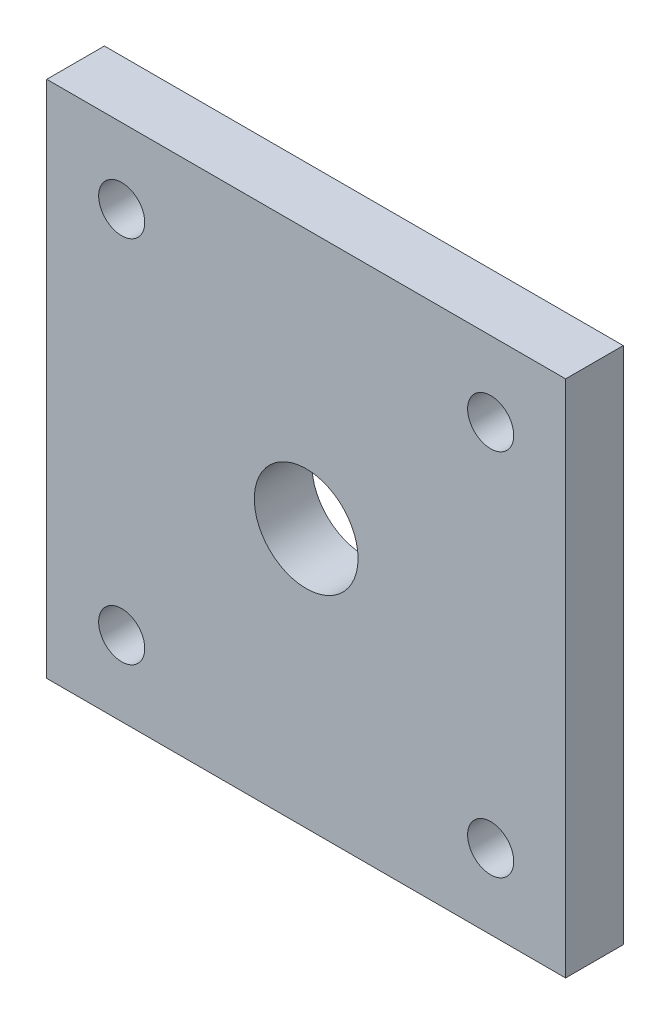
SolidWorks part; units mm, degrees
ref_plane "Front Plane" through (0, 0, 0) normal (0, 0, 1) x (1, 0, 0)
ref_plane "Top Plane" through (0, 0, 0) normal (0, 1, 0) x (1, 0, 0)
ref_plane "Right Plane" through (0, 0, 0) normal (1, 0, 0) x (0, 0, -1)
sketch "Sketch1" plane through (0, 0, 0) normal (0, 0, 1) x (1, 0, 0)
  line L1 (-22.5, -22.5) -> (22.5, -22.5)
  line L2 (-22.5, -22.5) -> (-22.5, 22.5)
  line L3 (-22.5, 22.5) -> (22.5, 22.5)
  line L4 (22.5, -22.5) -> (22.5, 22.5)
  line L5 (-22.5, -22.5) -> (22.5, 22.5) construction
  line L6 (-22.5, 22.5) -> (22.5, -22.5) construction
  circle A0 centre (0, 0) radius 4.5
  point P0 (0, 0)
  dimension "D3" = 9
  dimension "D1" = 45
  dimension "D2" = 45
extrude "Boss-Extrude1" add sketch "Sketch1" along normal blind 5
extrude "Cut-Extrude1" cut sketch "Sketch2" against normal through all
sketch "Sketch2" plane through (-496.0375, -95.1348, 0) normal (0, 0, -1) x (-1, 0, 0)
  arc A8 (-510.0375, 79.1348) -> (-514.0375, 79.1348) centre (-512.0375, 79.1348) ccw
  arc A9 (-514.0375, 79.1348) -> (-510.0375, 79.1348) centre (-512.0375, 79.1348) ccw
  arc A10 (-478.0375, 79.1348) -> (-482.0375, 79.1348) centre (-480.0375, 79.1348) ccw
  arc A11 (-482.0375, 79.1348) -> (-478.0375, 79.1348) centre (-480.0375, 79.1348) ccw
  arc A12 (-478.0375, 111.1348) -> (-482.0375, 111.1348) centre (-480.0375, 111.1348) ccw
  arc A13 (-482.0375, 111.1348) -> (-478.0375, 111.1348) centre (-480.0375, 111.1348) ccw
  arc A14 (-510.0375, 111.1348) -> (-514.0375, 111.1348) centre (-512.0375, 111.1348) ccw
  arc A15 (-514.0375, 111.1348) -> (-510.0375, 111.1348) centre (-512.0375, 111.1348) ccw
